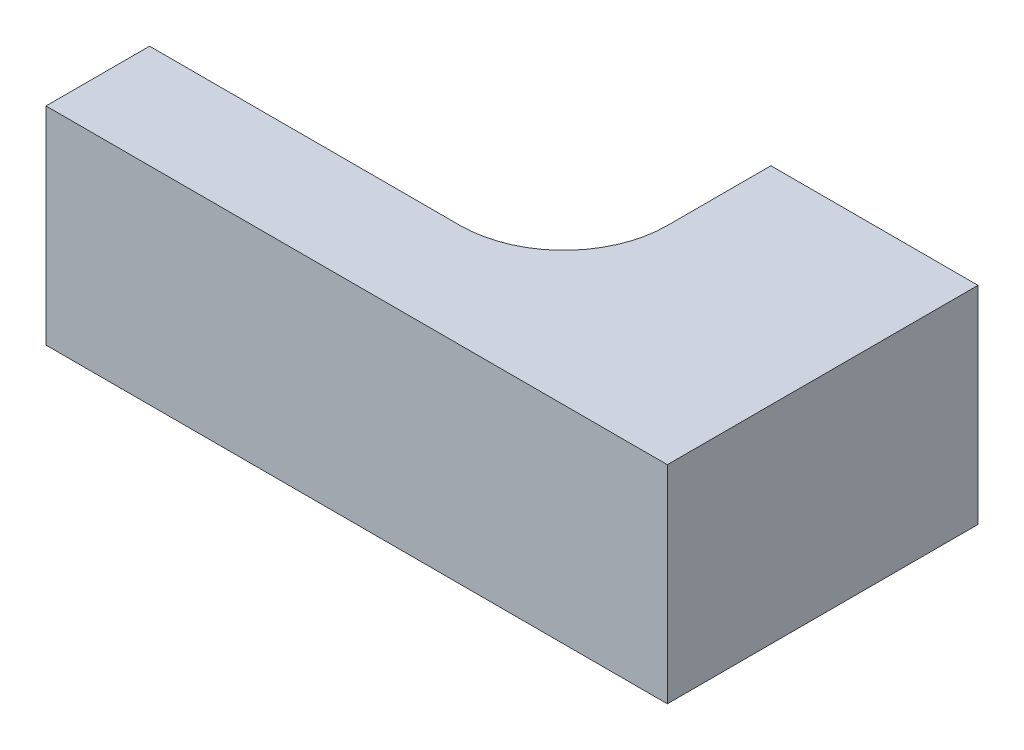
SolidWorks part; units mm, degrees
ref_plane "Přední rovina" through (0, 0, 0) normal (0, 0, 1) x (1, 0, 0)
ref_plane "Horní rovina" through (0, 0, 0) normal (0, 1, 0) x (1, 0, 0)
ref_plane "Pravá rovina" through (0, 0, 0) normal (1, 0, 0) x (0, 0, -1)
sketch "Sketch2" plane through (0, 0, 0) normal (0, 1, 0) x (1, 0, 0)
  line L0 (0, 0) -> (0, -10)
  line L1 (10, -20) -> (40, -20)
  line L2 (40, -20) -> (40, -30)
  line L3 (40, -30) -> (-20, -30)
  line L4 (-20, -30) -> (-20, 0)
  line L5 (-20, 0) -> (0, 0)
  arc A0 (0, -10) -> (10, -20) centre (10, -10) ccw
  dimension "D2" = 10
  dimension "D1" = 20
  dimension "D3" = 30
  dimension "D4" = 10
  dimension "D5" = 10
extrude "Boss-Extrude1" add sketch "Sketch2" along normal blind 20
mirror "Mirror1" about plane through (-20, 20, 30) normal (1, 0, 0) of bodies 101
delete or keep bodies "Body-Delete/Keep 1" type delete bodies bodies 101
equation "\"R\"= 10"
equation "\"D2@Sketch2\"=\"R\""
equation "\"D1@Sketch2\"=\"R\" *2"
equation "\"D3@Sketch2\"=\"R\" * 3"
equation "\"D5@Sketch2\"=\"R\""
equation "\"D4@Sketch2\"=\"R\""
